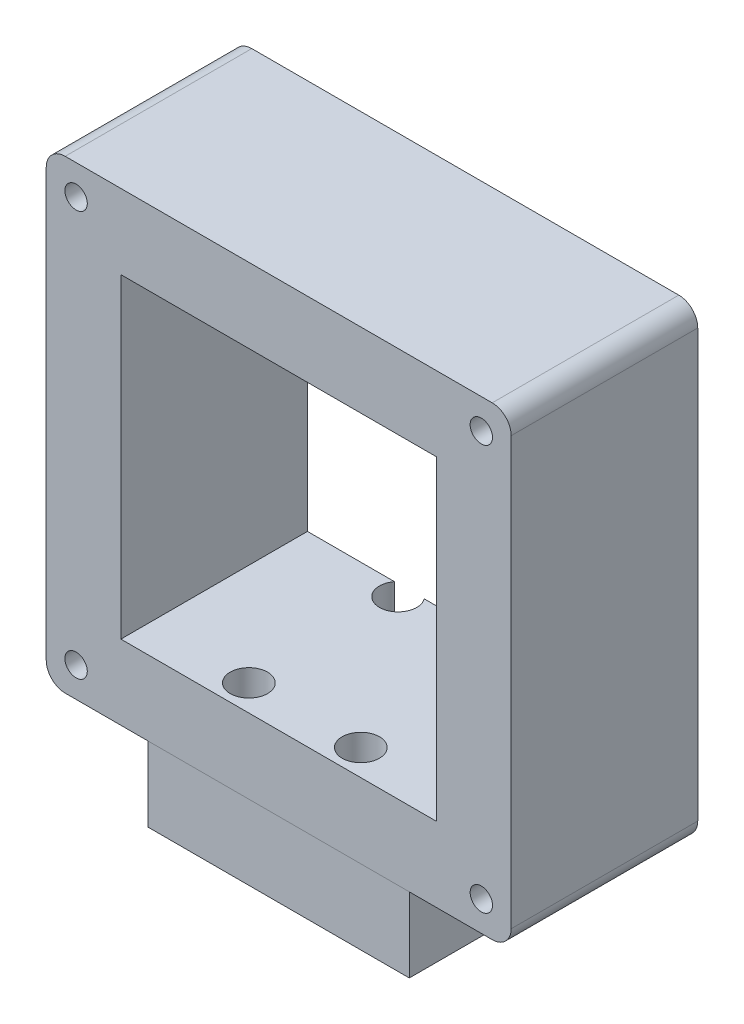
SolidWorks part; units mm, degrees
material "PLA"
ref_plane "Front Plane" through (0, 0, 0) normal (0, 0, 1) x (1, 0, 0)
ref_plane "Top Plane" through (0, 0, 0) normal (0, 1, 0) x (1, 0, 0)
ref_plane "Right Plane" through (0, 0, 0) normal (1, 0, 0) x (0, 0, -1)
sketch "Sketch1" plane through (0, 0, 0) normal (0, 1, 0) x (1, 0, 0)
  line L1 (-17.5, -13.5) -> (17.5, -13.5)
  line L2 (-17.5, -13.5) -> (-17.5, 13.5)
  line L3 (-17.5, 13.5) -> (17.5, 13.5)
  line L4 (17.5, -13.5) -> (17.5, 13.5)
  line L5 (-17.5, -13.5) -> (17.5, 13.5) construction
  line L6 (-17.5, 13.5) -> (17.5, -13.5) construction
  line L7 (-7.5, -10) -> (7.5, -10) construction
  line L8 (-7.5, -10) -> (-7.5, 10) construction
  line L9 (-7.5, 10) -> (7.5, 10) construction
  line L10 (7.5, -10) -> (7.5, 10) construction
  line L11 (-7.5, -10) -> (7.5, 10) construction
  line L12 (-7.5, 10) -> (7.5, -10) construction
  circle A0 centre (-7.5, 10) radius 1.5
  circle A1 centre (7.5, 10) radius 1.5
  circle A2 centre (7.5, -10) radius 1.5
  circle A3 centre (-7.5, -10) radius 1.5
  point P0 (0, 0)
  point P6 (0, 0)
  dimension "D5" = 3
  dimension "D1" = 35
  dimension "D2" = 27
  dimension "D3" = 15
  dimension "D4" = 20
extrude "Boss-Extrude1" add sketch "Sketch1" along normal mid plane 10
sketch "Sketch2" plane through (0, 0, 13.5) normal (0, 0, 1) x (1, 0, 0)
  line L1 (-21.15, 15) -> (21.15, 15)
  line L2 (-21.15, 15) -> (-21.15, 57.3)
  line L3 (-21.15, 57.3) -> (21.15, 57.3)
  line L4 (21.15, 15) -> (21.15, 57.3)
  line L5 (-21.15, 15) -> (21.15, 57.3) construction
  line L6 (-21.15, 57.3) -> (21.15, 15) construction
  line L7 (-31.15, 5) -> (31.15, 5)
  line L8 (-31.15, 5) -> (-31.15, 67.3)
  line L9 (-31.15, 67.3) -> (31.15, 67.3)
  line L10 (31.15, 5) -> (31.15, 67.3)
  line L11 (-31.15, 5) -> (31.15, 67.3) construction
  line L12 (-31.15, 67.3) -> (31.15, 5) construction
  line L15 (-17.5, 5) -> (17.5, 5) construction
  point P0 (0, 36.15)
  point P5 (0, 36.15)
  dimension "D1" = 42.3
  dimension "D2" = 42.3
  dimension "D3" = 10
  dimension "D4" = 10
extrude "Boss-Extrude2" add sketch "Sketch2" against normal blind 25 separate body
sketch "Sketch3" plane through (0, 5, 0) normal (0, -1, 0) x (1, 0, 0)
  circle A0 centre (-7.5, 10) radius 2.5
  circle A1 centre (7.5, 10) radius 2.5
  circle A2 centre (7.5, -10) radius 2.5
  circle A3 centre (-7.5, -10) radius 2.5
  dimension "D1" = 5
extrude "Cut-Extrude2" cut sketch "Sketch3" against normal up to surface (10 mm away) up to face at (0, 15, 1)
ref_plane "Plane1" through (0, 36.15, 0) normal (0, -1, 0) x (-1, 0, 0)
sketch "Sketch4" plane through (0, 0, 13.5) normal (0, 0, 1) x (1, 0, 0)
  line L0 (-13.75, 36.15) -> (13.75, 36.15) construction
  line L1 (-27.15, 9) -> (27.15, 9) construction
  line L2 (-27.15, 9) -> (-27.15, 63.3) construction
  line L3 (-27.15, 63.3) -> (27.15, 63.3) construction
  line L4 (27.15, 9) -> (27.15, 63.3) construction
  line L5 (-27.15, 9) -> (27.15, 63.3) construction
  line L6 (-27.15, 63.3) -> (27.15, 9) construction
  line L7 (-31.15, 67.3) -> (-31.15, 5) construction
  line L8 (31.15, 67.3) -> (-31.15, 67.3) construction
  circle A4 centre (-27.15, 63.3) radius 1.5
  circle A5 centre (27.15, 63.3) radius 1.5
  circle A6 centre (27.15, 9) radius 1.5
  circle A7 centre (-27.15, 9) radius 1.5
  point P0 (0, 36.15)
  dimension "D3" = 3
  dimension "D1" = 4
  dimension "D2" = 4
extrude "Cut-Extrude3" cut sketch "Sketch4" against normal blind 5
fillet "Fillet1" radius 2.54 4 edges at (31.15, 67.3, 1) (31.15, 5, 1) (-31.15, 67.3, 1) (-31.15, 5, 1)
